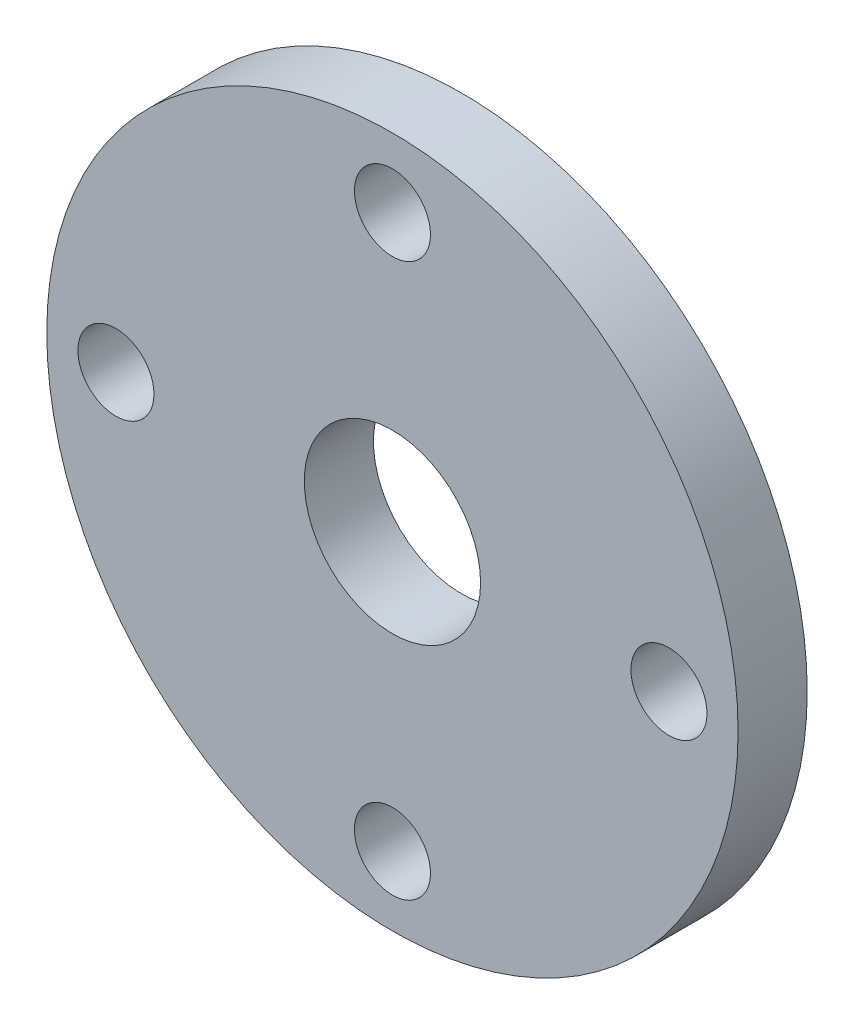
SolidWorks part; units mm, degrees
ref_plane "Front Plane" through (0, 0, 0) normal (0, 0, 1) x (1, 0, 0)
ref_plane "Top Plane" through (0, 0, 0) normal (0, 1, 0) x (1, 0, 0)
ref_plane "Right Plane" through (0, 0, 0) normal (1, 0, 0) x (0, 0, -1)
sketch "Horn_plate_envelope_profile" plane through (0, 0, 0) normal (0, 0, 1) x (1, 0, 0)
  circle A0 centre (0, 0) radius 10
  circle A1 centre (0, 0) radius 2.55
  dimension "D1" = 20
  dimension "D2" = 5.1
extrude "Horn_plate_envelope" add sketch "Horn_plate_envelope_profile" along normal blind 2
sketch "Nominal_horn_attachment_holes_profile" plane through (0, 0, 0) normal (0, 0, 1) x (1, 0, 0)
  circle A0 centre (-8, 0) radius 1.1
  circle A1 centre (8, 0) radius 1.1
  circle A2 centre (0, -8) radius 1.1
  circle A3 centre (0, 8) radius 1.1
  dimension "D1" = 2.2
  dimension "D2" = 2.2
  dimension "D3" = 2.2
  dimension "D4" = 2.2
extrude "Nominal_horn_attachment_holes" cut sketch "Nominal_horn_attachment_holes_profile" along normal through all from offset 50
